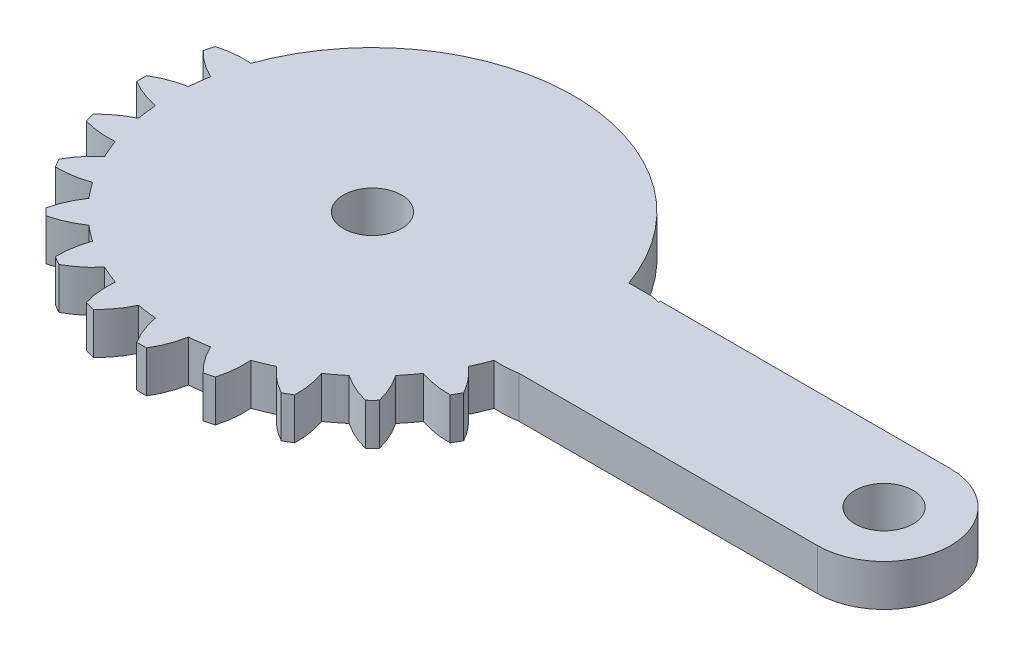
SolidWorks part; units mm, degrees
ref_plane "前视基准面" through (0, 0, 0) normal (0, 0, 1) x (1, 0, 0)
ref_plane "上视基准面" through (0, 0, 0) normal (0, 1, 0) x (1, 0, 0)
ref_plane "右视基准面" through (0, 0, 0) normal (1, 0, 0) x (0, 0, -1)
other "Configuration Table"
sketch "草图1" plane through (0, 0, 0) normal (0, 1, 0) x (1, 0, 0)
  line L0 (0, 0) -> (0, 55.5) construction
  line L1 (0, 0) -> (132.3795, 0) construction
  line L2 (45.6365, 16) -> (123, 16)
  line L3 (123, -16) -> (45.6365, -16)
  circle A0 centre (0, 0) radius 7
  circle A1 centre (0, 0) radius 48.36
  circle A2 centre (0, 0) radius 55.5
  arc A3 (1.19, 55.4872) -> (3.96, 48.1976) centre (-17.2847, 44.2959) cw
  arc A4 (-1.19, 55.4872) -> (-3.96, 48.1976) centre (17.2847, 44.2959) ccw
  arc A5 (13.2117, 53.9046) -> (8.6494, 47.5802) centre (28.1604, 38.313) ccw
  arc A6 (15.5106, 53.2886) -> (16.2995, 45.5304) centre (-5.2311, 47.2602) cw
  arc A7 (26.7131, 48.6484) -> (20.6693, 43.7203) centre (37.1169, 29.719) ccw
  arc A8 (28.7742, 47.4584) -> (27.5283, 39.7603) centre (7.179, 47.0037) cw
  arc A9 (38.3939, 40.0769) -> (31.2807, 36.881) centre (43.5441, 19.0998) ccw
  arc A10 (40.0769, 38.3939) -> (36.881, 31.2807) centre (19.0998, 43.5441) cw
  arc A11 (47.4584, 28.7742) -> (39.7603, 27.5283) centre (47.0037, 7.179) ccw
  arc A12 (48.6484, 26.7131) -> (43.7203, 20.6693) centre (29.719, 37.1169) cw
  arc A13 (53.2886, 15.5106) -> (45.5304, 16.2995) centre (47.2602, -5.2311) ccw
  arc A14 (53.9046, 13.2117) -> (47.5802, 8.6494) centre (38.313, 28.1604) cw
  arc A15 (55.4872, 1.19) -> (48.1976, 3.96) centre (44.2959, -17.2847) ccw
  arc A16 (55.4872, -1.19) -> (48.1976, -3.96) centre (44.2959, 17.2847) cw
  arc A17 (53.9046, -13.2117) -> (47.5802, -8.6494) centre (38.313, -28.1604) ccw
  arc A18 (53.2886, -15.5106) -> (45.5304, -16.2995) centre (47.2602, 5.2311) cw
  arc A19 (48.6484, -26.7131) -> (43.7203, -20.6693) centre (29.719, -37.1169) ccw
  arc A20 (47.4584, -28.7742) -> (39.7603, -27.5283) centre (47.0037, -7.179) cw
  arc A21 (40.0769, -38.3939) -> (36.881, -31.2807) centre (19.0998, -43.5441) ccw
  arc A22 (38.3939, -40.0769) -> (31.2807, -36.881) centre (43.5441, -19.0998) cw
  arc A23 (28.7742, -47.4584) -> (27.5283, -39.7603) centre (7.179, -47.0037) ccw
  arc A24 (26.7131, -48.6484) -> (20.6693, -43.7203) centre (37.1169, -29.719) cw
  arc A25 (15.5106, -53.2886) -> (16.2995, -45.5304) centre (-5.2311, -47.2602) ccw
  arc A26 (13.2117, -53.9046) -> (8.6494, -47.5802) centre (28.1604, -38.313) cw
  arc A27 (1.19, -55.4872) -> (3.96, -48.1976) centre (-17.2847, -44.2959) ccw
  arc A28 (-1.19, -55.4872) -> (-3.96, -48.1976) centre (17.2847, -44.2959) cw
  arc A29 (-13.2117, -53.9046) -> (-8.6494, -47.5802) centre (-28.1604, -38.313) ccw
  arc A30 (-15.5106, -53.2886) -> (-16.2995, -45.5304) centre (5.2311, -47.2602) cw
  arc A31 (-26.7131, -48.6484) -> (-20.6693, -43.7203) centre (-37.1169, -29.719) ccw
  arc A32 (-28.7742, -47.4584) -> (-27.5283, -39.7603) centre (-7.179, -47.0037) cw
  arc A33 (-38.3939, -40.0769) -> (-31.2807, -36.881) centre (-43.5441, -19.0998) ccw
  arc A34 (-40.0769, -38.3939) -> (-36.881, -31.2807) centre (-19.0998, -43.5441) cw
  arc A35 (-47.4584, -28.7742) -> (-39.7603, -27.5283) centre (-47.0037, -7.179) ccw
  arc A36 (-48.6484, -26.7131) -> (-43.7203, -20.6693) centre (-29.719, -37.1169) cw
  arc A37 (-53.2886, -15.5106) -> (-45.5304, -16.2995) centre (-47.2602, 5.2311) ccw
  arc A38 (-53.9046, -13.2117) -> (-47.5802, -8.6494) centre (-38.313, -28.1604) cw
  arc A39 (-55.4872, -1.19) -> (-48.1976, -3.96) centre (-44.2959, 17.2847) ccw
  arc A40 (-55.4872, 1.19) -> (-48.1976, 3.96) centre (-44.2959, -17.2847) cw
  arc A41 (-53.9046, 13.2117) -> (-47.5802, 8.6494) centre (-38.313, 28.1604) ccw
  arc A42 (-53.2886, 15.5106) -> (-45.5304, 16.2995) centre (-47.2602, -5.2311) cw
  arc A43 (-48.6484, 26.7131) -> (-43.7203, 20.6693) centre (-29.719, 37.1169) ccw
  arc A44 (-47.4584, 28.7742) -> (-39.7603, 27.5283) centre (-47.0037, 7.179) cw
  arc A45 (-40.0769, 38.3939) -> (-36.881, 31.2807) centre (-19.0998, 43.5441) ccw
  arc A46 (-38.3939, 40.0769) -> (-31.2807, 36.881) centre (-43.5441, 19.0998) cw
  arc A47 (-28.7742, 47.4584) -> (-27.5283, 39.7603) centre (-7.179, 47.0037) ccw
  arc A48 (-26.7131, 48.6484) -> (-20.6693, 43.7203) centre (-37.1169, 29.719) cw
  arc A49 (-15.5106, 53.2886) -> (-16.2995, 45.5304) centre (5.2311, 47.2602) ccw
  arc A50 (-13.2117, 53.9046) -> (-8.6494, 47.5802) centre (-28.1604, 38.313) cw
  arc A51 (123, 16) -> (123, -16) centre (123, 0) cw
  circle A52 centre (123, 0) radius 7
  point P152 (0, 0)
  point P158 (-71.2051, 28.9474)
  point P159 (-75.2892, 50.7152)
  dimension "D1" = 14
  dimension "D2" = 96.72
  dimension "D3" = 111
  dimension "D6" = 21.6
  dimension "D8" = 123
  dimension "D9" = 16
  dimension "D4" = 2.38
  dimension "D5" = 7.92
  dimension "D7" = 24
extrude "凸台-拉伸2" add sketch "草图1" along normal blind 10 contours A51 L2 A2 L3 A52 | A1 | A14 A2 A13 L2 A1 | A15 A2 A14 A1 | A16 A2 A15 A1 | A17 A2 A16 A1 | A18 A2 A17 A1 L3 | A18 L3 A1 | A2 A18 L3 | A20 A2 A19 A1 | A22 A2 A21 A1 | A24 A2 A23 A1 | A26 A2 A25 A1 | A28 A2 A27 A1 | A30 A2 A29 A1 | A32 A2 A31 A1 | A34 A2 A33 A1 | A36 A2 A35 A1 | A38 A2 A37 A1 | A40 A2 A39 A1 | A42 A2 A41 A1
